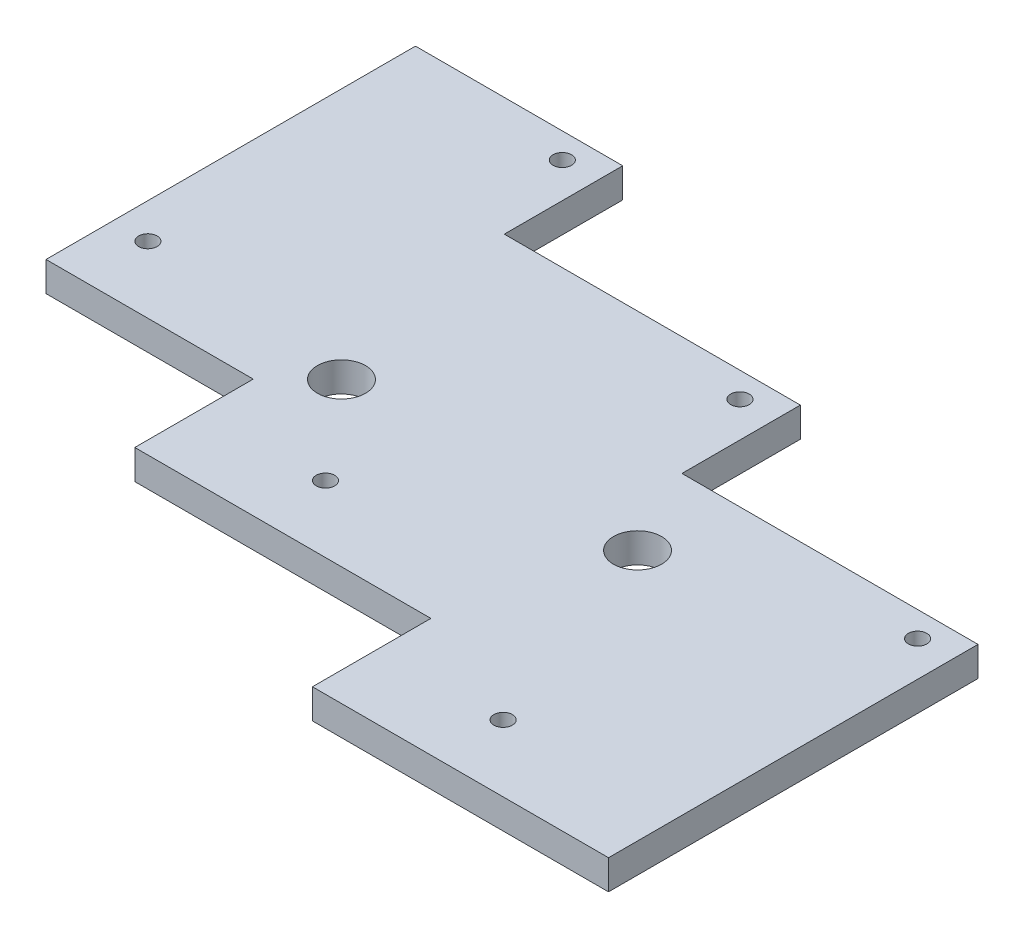
SolidWorks part; units mm, degrees
ref_plane "Front Plane" through (0, 0, 0) normal (0, 0, 1) x (1, 0, 0)
ref_plane "Top Plane" through (0, 0, 0) normal (0, 1, 0) x (1, 0, 0)
ref_plane "Right Plane" through (0, 0, 0) normal (1, 0, 0) x (0, 0, -1)
sketch "Sketch1" plane through (0, 0, 0) normal (0, 1, 0) x (1, 0, 0)
  line L0 (-85.725, -14.224) -> (-41.275, -14.224)
  line L1 (-41.275, -14.224) -> (-41.275, -39.624)
  line L2 (-41.275, -39.624) -> (22.225, -39.624)
  line L3 (22.225, -39.624) -> (22.225, -65.024)
  line L4 (22.225, -65.024) -> (85.725, -65.024)
  line L5 (85.725, -65.024) -> (85.725, 14.224)
  line L6 (85.725, 14.224) -> (22.225, 14.224)
  line L7 (22.225, 14.224) -> (22.225, 39.624)
  line L8 (22.225, 39.624) -> (-41.275, 39.624)
  line L9 (-41.275, 39.624) -> (-41.275, 65.024)
  line L10 (-41.275, 65.024) -> (-85.725, 65.024)
  line L11 (-85.725, 65.024) -> (-85.725, -14.224)
  point P12 (0, 0)
  dimension "D1" = 63.5
  dimension "D2" = 127
  dimension "D3" = 171.45
  dimension "D4" = 25.4
  dimension "D5" = 50.8
  dimension "D6" = 79.248
  dimension "D7" = 104.648
  dimension "D8" = 130.048
  dimension "D9" = 85.725
  dimension "D10" = 65.024
extrude "Boss-Extrude1" add sketch "Sketch1" along normal mid plane 6.35
sketch "Sketch2" plane through (0, 0, 0) normal (0, 1, 0) x (1, 0, 0)
  circle A0 centre (-31.75, -4.826) radius 5.1562
  circle A1 centre (31.75, -4.826) radius 5.1562
  point P4 (0, 0)
  dimension "D1" = 10.3124
  dimension "D2" = 10.3124
  dimension "D3" = 63.5
  dimension "D4" = 31.75
  dimension "D5" = 4.826
extrude "Cut-Extrude2" cut sketch "Sketch2" against normal through all from offset 3.175
hole_wizard "#10-24 Tapped Hole1" positions "Sketch4" profile "Sketch3" tap size "#10-24" standard "ANSI Inch"
sketch "Sketch4" plane through (0, 3.175, 0) normal (0, 1, 0) x (1, 0, 0)
  line L0 (0, 0) -> (-48.8188, 59.6138) construction
  line L1 (22.225, -39.624) -> (22.225, -65.024) construction
  line L2 (-41.275, -39.624) -> (22.225, -39.624) construction
  point P0 (-78.1812, 0.0762)
  point P1 (-48.8188, 59.6138)
  point P3 (-14.6812, -25.3238)
  point P5 (14.6812, 34.2138)
  point P7 (48.8188, -50.7238)
  point P9 (78.1812, 8.8138)
  dimension "D1" = 26.5938
  dimension "D2" = 55.9562
  dimension "D3" = 7.5438
  dimension "D4" = 36.9062
  dimension "D5" = 71.0438
  dimension "D6" = 100.4062
  dimension "D7" = 14.3002
  dimension "D8" = 39.7002
  dimension "D9" = 48.4378
  dimension "D10" = 73.8378
  dimension "D11" = 99.2378
  dimension "D12" = 11.0998
sketch "Sketch3" plane through (-78.1812, 3.175, -0.0762) normal (1, 0, 0) x (0, 0, 1)
  line L0 (0, 0) -> (0, 7.5404)
  line L1 (0, 7.5404) -> (1.9812, 6.35)
  line L2 (1.9812, 6.35) -> (1.9812, 0)
  line L5 (1.9812, 0) -> (0, 0)
  line L10 (0, 7.5404) -> (-1.9812, 6.35) construction
  line L11 (0, -6.35) -> (0, 107.95) construction
  dimension "Tap Drill Dia." = 3.9624
  dimension "Tap Drill Depth" = 6.35
  dimension "Drill Angle" = 118
cosmetic thread "Hole Thread1" parameters "D1"=9.652, "D2"=4.826
cosmetic thread "Hole Thread2" parameters "D1"=9.652, "D2"=4.826
cosmetic thread "Hole Thread3" parameters "D1"=9.652, "D2"=4.826
cosmetic thread "Hole Thread4" parameters "D1"=9.652, "D2"=4.826
cosmetic thread "Hole Thread5" parameters "D1"=9.652, "D2"=4.826
cosmetic thread "Hole Thread6" parameters "D1"=9.652, "D2"=4.826
